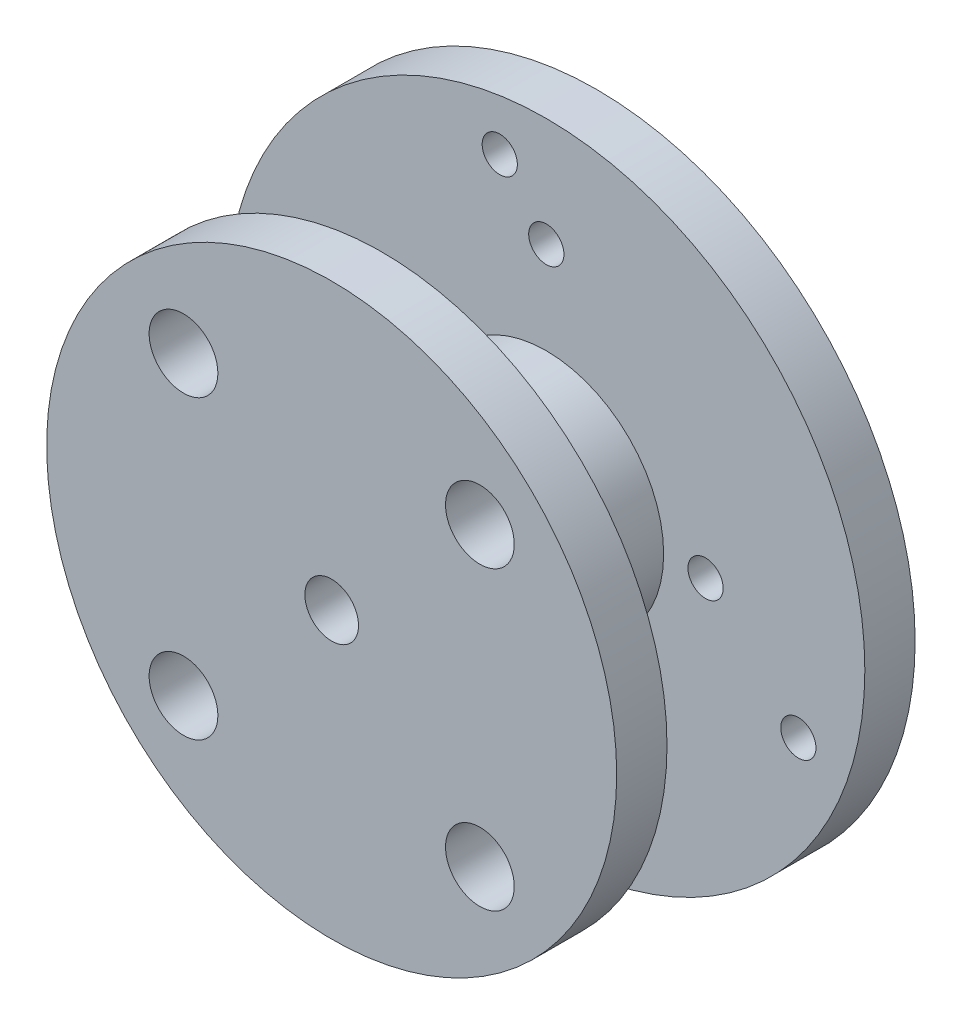
SolidWorks part; units mm, degrees
material "1345 合金"
ref_plane "前视基准面" through (0, 0, 0) normal (0, 0, 1) x (1, 0, 0)
ref_plane "上视基准面" through (0, 0, 0) normal (0, 1, 0) x (1, 0, 0)
ref_plane "右视基准面" through (0, 0, 0) normal (1, 0, 0) x (0, 0, -1)
sketch "草图1" plane through (0, 0, 0) normal (0, 0, 1) x (1, 0, 0)
  circle A0 centre (0, 0) radius 19
  dimension "D1" = 38
extrude "凸台-拉伸1" add sketch "草图1" along normal blind 3
sketch "草图2" plane through (0, 0, 3) normal (0, 0, 1) x (1, 0, 0)
  circle A0 centre (0, 0) radius 12.5 construction
  circle A1 centre (0, 0) radius 9.5 construction
  circle A2 centre (0, 0) radius 16 construction
  circle A3 centre (0, 12.5) radius 1.05
  circle A4 centre (-9.5, 0) radius 1.05
  circle A5 centre (9.5, 0) radius 1.05
  circle A6 centre (0, -12.5) radius 1.05
  circle A7 centre (-2.7764, 15.7573) radius 1.05
  circle A8 centre (15.0344, -5.4742) radius 1.05
  circle A9 centre (-12.258, -10.2831) radius 1.05
  point P21 (0, 0)
  dimension "D1" = 32
  dimension "D2" = 25
  dimension "D3" = 19
  dimension "D4" = 2.1
  dimension "D5" = 2.1
  dimension "D6" = 4.28
  dimension "D7" = 3
extrude "切除-拉伸1" cut sketch "草图2" against normal through all
sketch "草图3" plane through (0, 0, 3) normal (0, 0, 1) x (1, 0, 0)
  circle A0 centre (0, 0) radius 7
  dimension "D1" = 14
extrude "凸台-拉伸2" add sketch "草图3" along normal blind 9.8
sketch "草图4" plane through (0, 0, 12.8) normal (0, 0, 1) x (1, 0, 0)
  circle A0 centre (0, 0) radius 17
  dimension "D1" = 34
extrude "凸台-拉伸3" add sketch "草图4" along normal blind 3
sketch "草图5" plane through (0, 0, 15.8) normal (0, 0, 1) x (1, 0, 0)
  circle A0 centre (0, 0) radius 1.6 construction
  dimension "D1" = 3.2
hole_wizard "Ø3.2 (3.2) 直径孔1" positions "3D草图1" profile "草图6" hole size "Ø3.2" standard "ANSI Metric"
sketch3d "3D草图1"
  point P0 (0, 0, 15.8)
sketch "草图6" plane through (0, 0, 15.8) normal (1, 0, 0) x (0, -1, 0)
  line L0 (0, 0) -> (0, 6.9614)
  line L1 (0, 6.9614) -> (1.6, 6)
  line L2 (1.6, 6) -> (1.6, 0)
  line L5 (1.6, 0) -> (0, 0)
  line L10 (0, 6.9614) -> (-1.6, 6) construction
  line L11 (0, -6.35) -> (0, 107.95) construction
  dimension "孔直径" = 3.2
  dimension "孔深度" = 6
  dimension "导头角度" = 118
sketch "草图7" plane through (0, 0, 0) normal (0, 0, -1) x (-1, 0, 0)
  circle A0 centre (0, 0) radius 3
  dimension "D1" = 6
extrude "切除-拉伸2" cut sketch "草图7" against normal blind 4
sketch "草图8" plane through (0, 0, 15.8) normal (0, 0, 1) x (1, 0, 0)
  line L0 (0, 0) -> (8.8388, 8.8388) construction
  line L1 (0, -12.5) -> (0, 12.5) construction
  circle A0 centre (8.8388, 8.8388) radius 2.05
  circle A1 centre (0, 0) radius 12.5 construction
  circle A2 centre (8.8388, -8.8388) radius 2.05
  circle A3 centre (-8.8388, -8.8388) radius 2.05
  circle A4 centre (-8.8388, 8.8388) radius 2.05
  point P16 (0, 0)
  dimension "D1" = 25
  dimension "D2" = 4.1
  dimension "D3" = 45
  dimension "D4" = 4
extrude "切除-拉伸3" cut sketch "草图8" against normal blind 4
